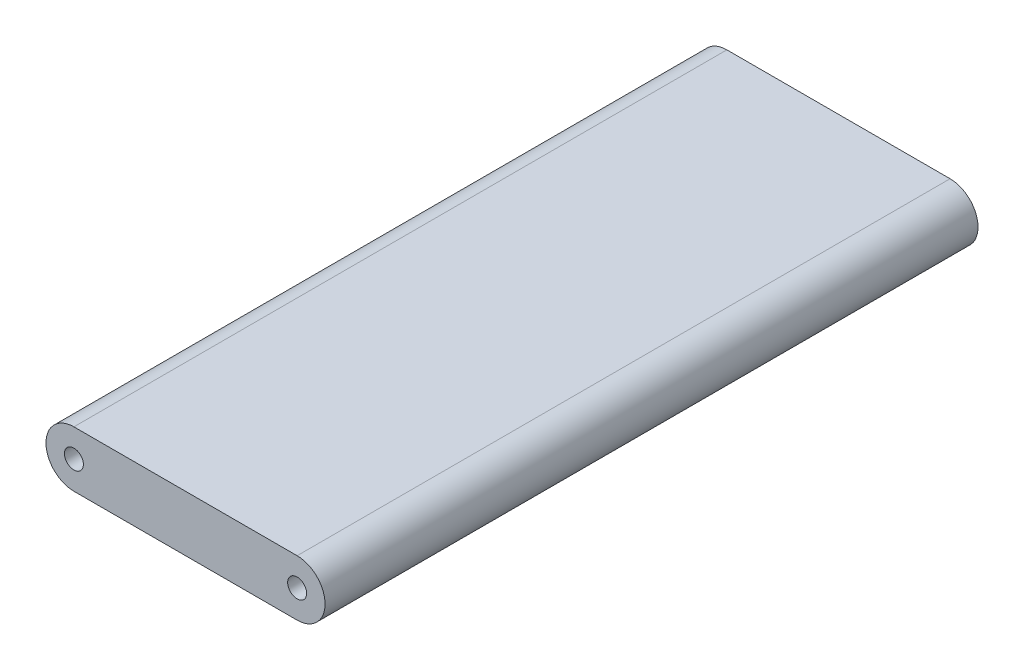
SolidWorks part; units mm, degrees
material "ABS"
ref_plane "正面" through (0, 0, 0) normal (0, 0, 1) x (1, 0, 0)
ref_plane "平面" through (0, 0, 0) normal (0, 1, 0) x (1, 0, 0)
ref_plane "右側面" through (0, 0, 0) normal (1, 0, 0) x (0, 0, -1)
sketch "ｽｹｯﾁ1" plane through (0, 0, 0) normal (0, 0, 1) x (1, 0, 0)
  line L0 (0, 2.5) -> (20, 2.5)
  line L1 (0, -2.5) -> (20, -2.5)
  circle A0 centre (0, 0) radius 0.85
  arc A1 (0, 2.5) -> (0, -2.5) centre (0, 0) ccw
  arc A2 (20, -2.5) -> (20, 2.5) centre (20, 0) ccw
  circle A3 centre (20, 0) radius 0.85
  dimension "D1" = 1.7
  dimension "D2" = 20
  dimension "5" = 5
extrude "ﾎﾞｽ - 押し出し1" add sketch "ｽｹｯﾁ1" along normal blind 58.5
